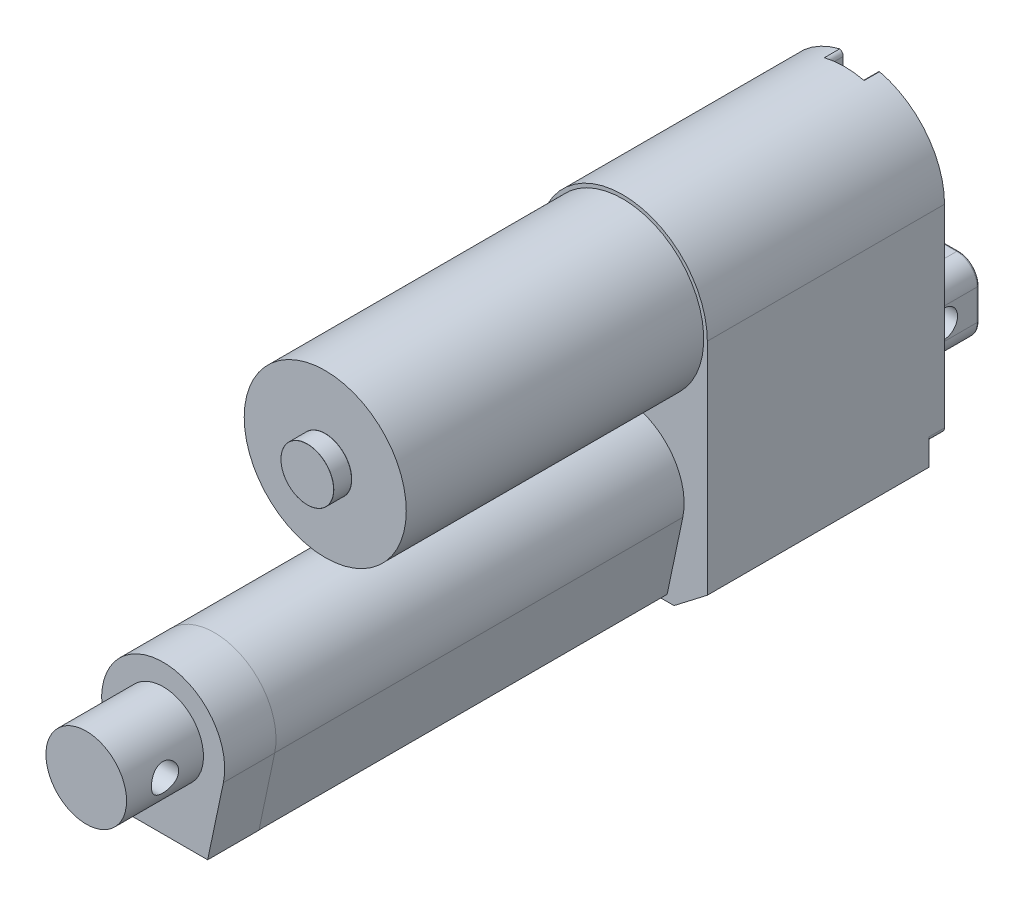
SolidWorks part; units mm, degrees
ref_plane "Front Plane" through (0, 0, 0) normal (0, 0, 1) x (1, 0, 0)
ref_plane "Top Plane" through (0, 0, 0) normal (0, 1, 0) x (1, 0, 0)
ref_plane "Right Plane" through (0, 0, 0) normal (1, 0, 0) x (0, 0, -1)
sketch "Sketch1" plane through (0, 0, 0) normal (0, 0, 1) x (1, 0, 0)
  line L0 (-12.7, 0) -> (12.7, 0)
  line L1 (-20.955, 6.35) -> (-20.955, 60.833)
  line L2 (20.955, 6.35) -> (20.955, 60.833)
  line L3 (12.7, 0) -> (20.955, 6.35)
  line L4 (-20.955, 6.35) -> (-12.7, 0)
  arc A0 (-20.955, 60.833) -> (20.955, 60.833) centre (0, 60.833) cw
  point P0 (0, 81.788)
  dimension "D7" = 81.788
  dimension "D1" = 41.91
  dimension "D2" = 8.255
  dimension "D3" = 12.7
  dimension "D4" = 8.255
  dimension "D5" = 12.7
  dimension "D6" = 6.35
extrude "Boss-Extrude1" add sketch "Sketch1" along normal blind 58.7375
sketch "Sketch2" plane through (0, 0, 58.7375) normal (0, 0, 1) x (1, 0, 0)
  circle A0 centre (0, 60.833) radius 20.066
  arc A1 (20.955, 60.833) -> (-20.955, 60.833) centre (0, 60.833) ccw construction
  dimension "D1" = 40.132
extrude "Boss-Extrude2" add sketch "Sketch2" along normal blind 73.66
sketch "Sketch3" plane through (0, 0, 58.7375) normal (0, 0, 1) x (1, 0, 0)
  line L0 (-12.7, 0) -> (12.7, 0) construction
  line L1 (-14.8881, 20.0427) -> (-10.9969, 1.5621)
  line L2 (-10.9969, 1.5621) -> (10.9969, 1.5621)
  line L3 (10.9969, 1.5621) -> (14.8881, 20.0427)
  line L5 (-10.9969, 1.5621) -> (-10.668, 0) construction
  line L6 (10.9969, 1.5621) -> (10.668, 0) construction
  arc A0 (14.8881, 20.0427) -> (-14.8881, 20.0427) centre (0, 23.1775) ccw
  point P1 (0, 1.5621)
  point P6 (15.2146, 23.1775)
  point P11 (-15.2146, 23.1775)
  point P16 (0, 38.3921)
  dimension "D1" = 23.1775
  dimension "D3" = 36.83
  dimension "D2" = 30.4292
  dimension "D4" = 21.336
extrude "EDIT_LENGTH_HERE (hover for comment)" add sketch "Sketch3" along normal blind 113.792
sketch "Sketch4" plane through (0, 0, 172.5295) normal (0, 0, 1) x (1, 0, 0)
  circle A0 centre (0, 23.1775) radius 9.9822
  arc A1 (14.8881, 20.0427) -> (-14.8881, 20.0427) centre (0, 23.1775) ccw construction
  dimension "D3" = 19.9644
extrude "Boss-Extrude4" add sketch "Sketch4" along normal blind 19.05
sketch "Sketch5" plane through (0, 0, 0) normal (0, 0, -1) x (-1, 0, 0)
  line L0 (12.7, 0) -> (-12.7, 0) construction
  line L1 (-3.81, 32.0675) -> (3.81, 32.0675)
  line L2 (-8.89, 26.9875) -> (-8.89, 19.3675)
  line L3 (-3.81, 14.2875) -> (3.81, 14.2875)
  line L4 (8.89, 26.9875) -> (8.89, 19.3675)
  line L5 (-8.89, 32.0675) -> (8.89, 14.2875) construction
  line L6 (-8.89, 14.2875) -> (8.89, 32.0675) construction
  arc A0 (-8.89, 19.3675) -> (-3.81, 14.2875) centre (-3.81, 19.3675) ccw
  arc A1 (3.81, 14.2875) -> (8.89, 19.3675) centre (3.81, 19.3675) ccw
  arc A2 (3.81, 32.0675) -> (8.89, 26.9875) centre (3.81, 26.9875) cw
  arc A3 (-3.81, 32.0675) -> (-8.89, 26.9875) centre (-3.81, 26.9875) ccw
  point P0 (0, 23.1775)
  dimension "D4" = 5.08
  dimension "D1" = 17.78
  dimension "D2" = 17.78
  dimension "D3" = 14.2875
extrude "Boss-Extrude5" add sketch "Sketch5" along normal blind 20.6502
sketch "Sketch6" plane through (8.89, 0, 0) normal (1, 0, 0) x (0, 0, -1)
  line L0 (11.9062, 14.2875) -> (11.9062, 32.0675) construction
  line L1 (0, 26.9875) -> (0, 19.3675) construction
  line L2 (20.6502, 14.2875) -> (0, 14.2875) construction
  line L3 (-191.5795, 33.1597) -> (-191.5795, 13.1953) construction
  line L4 (20.6502, 32.0675) -> (0, 32.0675) construction
  circle A0 centre (11.9062, 23.1775) radius 3.3782
  circle A1 centre (-182.0545, 23.1775) radius 3.3782
  dimension "D1" = 6.7564
  dimension "D3" = 6.7564
  dimension "D2" = 11.9062
  dimension "D4" = 9.525
extrude "Cut-Extrude3" cut sketch "Sketch6" against normal through all and the other way through all
fillet "Fillet1" radius 2.54 8 edges at (-7.4021, 15.7754, 0) (0, 14.2875, 0) (7.4021, 15.7754, 0) (8.89, 23.1775, 0) (7.4021, 30.5796, 0) (0, 32.0675, 0) (-7.4021, 30.5796, 0) (-8.89, 23.1775, 0)
fillet "Fillet2" radius 0.508 8 edges at (8.89, 23.1775, -20.6502) (7.4021, 30.5796, -20.6502) (0, 32.0675, -20.6502) (-7.4021, 30.5796, -20.6502) (-8.89, 23.1775, -20.6502) (-7.4021, 15.7754, -20.6502) (0, 14.2875, -20.6502) (7.4021, 15.7754, -20.6502)
sketch "Sketch7" plane through (0, 0, 0) normal (0, 0, -1) x (-1, 0, 0)
  line L0 (-4.1275, 77.089) -> (-4.1275, 80.0683)
  line L1 (4.1275, 77.089) -> (4.1275, 79.9786)
  line L2 (-20.955, 6.35) -> (-20.955, 60.833) construction
  line L3 (20.955, 60.833) -> (20.955, 6.35) construction
  line L4 (-13.3956, 1.8544) -> (-11.2223, 6.0477)
  line L5 (-14.605, 11.6109) -> (-19.685, 11.6109)
  line L6 (11.5416, 5.5356) -> (13.4023, 1.8413)
  line L7 (14.605, 11.6109) -> (19.685, 11.6109)
  line L8 (20.955, 6.35) -> (12.7, 0) construction
  line L9 (-12.7, 0) -> (-20.955, 6.35) construction
  line L10 (-20.955, 6.35) -> (-20.955, 12.8809)
  line L11 (12.7, 0) -> (-12.7, 0) construction
  line L12 (-12.7, 0) -> (-20.955, 6.35)
  line L13 (20.955, 12.8809) -> (20.955, 6.35)
  line L14 (20.955, 6.35) -> (12.7, 0)
  arc A0 (-4.1275, 77.089) -> (4.1275, 77.089) centre (0, 77.089) ccw
  arc A1 (20.955, 60.833) -> (-20.955, 60.833) centre (0, 60.833) ccw construction
  arc A2 (6.3689, 80.7967) -> (-6.4572, 80.7683) centre (0, 60.833) ccw
  arc A3 (-6.4572, 80.7683) -> (-4.1275, 80.0683) centre (-5.3975, 80.0683) cw
  arc A4 (4.1275, 79.9786) -> (6.3689, 80.7967) centre (5.3975, 79.9786) cw
  arc A5 (-11.2223, 6.0477) -> (-14.605, 11.6109) centre (-14.605, 7.8009) ccw
  arc A6 (14.605, 11.6109) -> (11.5416, 5.5356) centre (14.605, 7.8009) ccw
  arc A7 (13.4023, 1.8413) -> (12.268, 0) centre (12.268, 1.27) cw
  arc A8 (-13.3956, 1.8544) -> (-12.268, 0) centre (-12.268, 1.27) ccw
  arc A9 (19.685, 11.6109) -> (20.955, 12.8809) centre (19.685, 12.8809) ccw
  arc A10 (-19.685, 11.6109) -> (-20.955, 12.8809) centre (-19.685, 12.8809) cw
  point P12 (4.6513, 81.2653)
  point P39 (20.955, 11.6109)
  point P42 (-20.955, 11.6109)
  line M10 (20.955, 6.35) -> (20.955, 60.833)
  arc M11 (20.955, 60.833) -> (-20.955, 60.833) centre (0, 60.833) ccw
  line M12 (-20.955, 60.833) -> (-20.955, 6.35)
  line M13 (-20.955, 6.35) -> (-12.7, 0)
  dimension "D1" = 8.255
  dimension "D2" = 1.27
  dimension "D3" = 1.27
  dimension "D5" = 7.62
  dimension "D8" = 1.27
  dimension "D9" = 1.27
  dimension "D4" = 16.256
  dimension "D6" = 6.35
  dimension "D7" = 6.35
extrude "Cut-Extrude5" cut sketch "Sketch7" against normal blind 3.81 contours L1 A4 A3 L0 A0 M11 | L5 A10 A8 L4 A5 M12 M13 | A9 L7 A6 L6 A7 L14 M10
sketch "Sketch8" plane through (0, 0, 132.3975) normal (0, 0, 1) x (1, 0, 0)
  circle A0 centre (0, 60.833) radius 6.5405
  dimension "D1" = 13.081
extrude "Boss-Extrude6" add sketch "Sketch8" along normal blind 4.445
fillet "Fillet3" radius 0.0254 2 edges at (6.5405, 60.833, 132.3975) (6.5405, 60.833, 136.8425)
sketch "Sketch9" plane through (0, 0, 172.5295) normal (0, 0, 1) x (1, 0, 0)
  line L0 (10.9969, 1.5621) -> (14.8881, 20.0427) construction
  line L1 (-14.8881, 20.0427) -> (-10.9969, 1.5621) construction
  line L2 (-10.9969, 1.5621) -> (10.9969, 1.5621) construction
  line L3 (10.9969, 1.5621) -> (14.8881, 20.0427)
  line L4 (-14.8881, 20.0427) -> (-10.9969, 1.5621)
  line L5 (-10.9969, 1.5621) -> (10.9969, 1.5621)
  line L6 (-11.0175, 1.5367) -> (11.0175, 1.5367)
  line L7 (11.0175, 1.5367) -> (14.913, 20.0374)
  line L8 (-14.913, 20.0374) -> (-11.0175, 1.5367)
  arc A0 (14.8881, 20.0427) -> (-14.8881, 20.0427) centre (0, 23.1775) ccw construction
  arc A1 (14.8881, 20.0427) -> (-14.8881, 20.0427) centre (0, 23.1775) ccw
  arc A2 (14.913, 20.0374) -> (-14.913, 20.0374) centre (0, 23.1775) ccw
  dimension "D1" = 0.0254
extrude "Boss-Extrude7" add sketch "Sketch9" against normal blind 12.7
sketch "Sketch10" plane through (0, 0, 3.81) normal (0, 0, -1) x (-1, 0, 0)
  circle A0 centre (0, 77.089) radius 2.54
  circle A1 centre (-14.605, 7.8009) radius 2.54
  circle A2 centre (14.605, 7.8009) radius 2.54
  dimension "D1" = 5.08
extrude "Boss-Extrude8" add sketch "Sketch10" along normal blind 0.635
sketch "Sketch12" plane through (0, 0, 3.175) normal (0, 0, -1) x (-1, 0, 0)
  line L0 (0.3175, 74.3343) -> (0.3175, 75.8444)
  line L1 (-0.2921, 78.359) -> (0.2921, 78.359)
  line L2 (-0.3175, 78.3336) -> (-0.3175, 77.5335)
  line L3 (-0.2921, 75.819) -> (0.2921, 75.819)
  line L4 (0.3175, 78.3336) -> (0.3175, 77.5335)
  line L5 (-0.3175, 78.359) -> (0.3175, 75.819) construction
  line L6 (-0.3175, 75.819) -> (0.3175, 78.359) construction
  line L7 (-1.2446, 77.4065) -> (-0.4445, 77.4065)
  line L8 (-1.27, 77.3811) -> (-1.27, 76.7969)
  line L9 (-1.2446, 76.7715) -> (-0.4445, 76.7715)
  line L10 (1.27, 77.3811) -> (1.27, 76.7763)
  line L11 (-1.27, 77.4065) -> (1.27, 76.7715) construction
  line L12 (-1.27, 76.7715) -> (1.27, 77.4065) construction
  line L13 (0.3264, 74.381) -> (1.2682, 76.767)
  line L14 (-14.2875, 7.3564) -> (-14.2875, 6.5563)
  line L15 (0.4445, 77.4065) -> (1.2446, 77.4065)
  line L16 (-0.3175, 76.6445) -> (-0.3175, 75.8444)
  line L17 (-14.8971, 9.0709) -> (-14.3129, 9.0709)
  line L18 (-14.9225, 9.0455) -> (-14.9225, 8.2454)
  line L19 (-14.8971, 6.5309) -> (-14.3129, 6.5309)
  line L20 (-14.2875, 9.0455) -> (-14.2875, 8.2454)
  line L21 (-14.9225, 9.0709) -> (-14.2875, 6.5309) construction
  line L22 (-14.9225, 6.5309) -> (-14.2875, 9.0709) construction
  line L23 (-15.8496, 8.1184) -> (-15.0495, 8.1184)
  line L24 (-15.875, 8.093) -> (-15.875, 7.5088)
  line L25 (-15.8496, 7.4834) -> (-15.0495, 7.4834)
  line L26 (-13.335, 8.093) -> (-13.335, 7.5088)
  line L27 (-15.875, 8.1184) -> (-13.335, 7.4834) construction
  line L28 (-15.875, 7.4834) -> (-13.335, 8.1184) construction
  line L29 (-14.1605, 7.4834) -> (-13.3604, 7.4834)
  line L30 (-14.1605, 8.1184) -> (-13.3604, 8.1184)
  line L31 (-14.9225, 7.3564) -> (-14.9225, 6.5563)
  line L32 (14.9225, 7.3564) -> (14.9225, 6.5563)
  line L33 (14.3129, 9.0709) -> (14.8971, 9.0709)
  line L34 (14.2875, 9.0455) -> (14.2875, 8.2454)
  line L35 (14.3129, 6.5309) -> (14.8971, 6.5309)
  line L36 (14.9225, 9.0455) -> (14.9225, 8.2454)
  line L37 (14.2875, 9.0709) -> (14.9225, 6.5309) construction
  line L38 (14.2875, 6.5309) -> (14.9225, 9.0709) construction
  line L39 (13.3604, 8.1184) -> (14.1605, 8.1184)
  line L40 (13.335, 8.093) -> (13.335, 7.5088)
  line L41 (13.3604, 7.4834) -> (14.1605, 7.4834)
  line L42 (15.875, 8.093) -> (15.875, 7.5088)
  line L43 (13.335, 8.1184) -> (15.875, 7.4834) construction
  line L44 (13.335, 7.4834) -> (15.875, 8.1184) construction
  line L45 (15.0495, 7.4834) -> (15.8496, 7.4834)
  line L46 (15.0495, 8.1184) -> (15.8496, 8.1184)
  line L47 (14.2875, 7.3564) -> (14.2875, 6.5055)
  arc A0 (-0.4445, 76.7715) -> (-0.3175, 76.6445) centre (-0.4445, 76.6445) cw
  arc A1 (0.3264, 74.381) -> (0.3175, 74.3343) centre (0.4445, 74.3343) ccw
  arc A2 (0.3175, 77.5335) -> (0.4445, 77.4065) centre (0.4445, 77.5335) ccw
  arc A3 (-0.4445, 77.4065) -> (-0.3175, 77.5335) centre (-0.4445, 77.5335) ccw
  arc A4 (-1.2446, 77.4065) -> (-1.27, 77.3811) centre (-1.2446, 77.3811) ccw
  arc A5 (-1.27, 76.7969) -> (-1.2446, 76.7715) centre (-1.2446, 76.7969) ccw
  arc A6 (-0.3175, 75.8444) -> (-0.2921, 75.819) centre (-0.2921, 75.8444) ccw
  arc A7 (0.2921, 75.819) -> (0.3175, 75.8444) centre (0.2921, 75.8444) ccw
  arc A8 (1.2682, 76.767) -> (1.27, 76.7763) centre (1.2446, 76.7763) ccw
  arc A9 (1.2446, 77.4065) -> (1.27, 77.3811) centre (1.2446, 77.3811) cw
  arc A10 (0.2921, 78.359) -> (0.3175, 78.3336) centre (0.2921, 78.3336) cw
  arc A11 (-0.2921, 78.359) -> (-0.3175, 78.3336) centre (-0.2921, 78.3336) ccw
  arc A12 (-15.0495, 7.4834) -> (-14.9225, 7.3564) centre (-15.0495, 7.3564) cw
  arc A13 (-14.1605, 7.4834) -> (-14.2875, 7.3564) centre (-14.1605, 7.3564) ccw
  arc A14 (-14.2875, 8.2454) -> (-14.1605, 8.1184) centre (-14.1605, 8.2454) ccw
  arc A15 (-15.0495, 8.1184) -> (-14.9225, 8.2454) centre (-15.0495, 8.2454) ccw
  arc A16 (-15.8496, 8.1184) -> (-15.875, 8.093) centre (-15.8496, 8.093) ccw
  arc A17 (-15.875, 7.5088) -> (-15.8496, 7.4834) centre (-15.8496, 7.5088) ccw
  arc A18 (-14.9225, 6.5563) -> (-14.8971, 6.5309) centre (-14.8971, 6.5563) ccw
  arc A19 (-14.3129, 6.5309) -> (-14.2875, 6.5563) centre (-14.3129, 6.5563) ccw
  arc A20 (-13.3604, 7.4834) -> (-13.335, 7.5088) centre (-13.3604, 7.5088) ccw
  arc A21 (-13.3604, 8.1184) -> (-13.335, 8.093) centre (-13.3604, 8.093) cw
  arc A22 (-14.3129, 9.0709) -> (-14.2875, 9.0455) centre (-14.3129, 9.0455) cw
  arc A23 (-14.8971, 9.0709) -> (-14.9225, 9.0455) centre (-14.8971, 9.0455) ccw
  arc A26 (14.1605, 7.4834) -> (14.2875, 7.3564) centre (14.1605, 7.3564) cw
  arc A27 (15.0495, 7.4834) -> (14.9225, 7.3564) centre (15.0495, 7.3564) ccw
  arc A28 (14.9225, 8.2454) -> (15.0495, 8.1184) centre (15.0495, 8.2454) ccw
  arc A29 (14.1605, 8.1184) -> (14.2875, 8.2454) centre (14.1605, 8.2454) ccw
  arc A30 (13.3604, 8.1184) -> (13.335, 8.093) centre (13.3604, 8.093) ccw
  arc A31 (13.335, 7.5088) -> (13.3604, 7.4834) centre (13.3604, 7.5088) ccw
  arc A32 (14.2875, 6.5055) -> (14.3129, 6.5309) centre (14.3129, 6.5055) ccw
  arc A33 (14.8971, 6.5309) -> (14.9225, 6.5563) centre (14.8971, 6.5563) ccw
  arc A34 (15.8496, 7.4834) -> (15.875, 7.5088) centre (15.8496, 7.5088) ccw
  arc A35 (15.8496, 8.1184) -> (15.875, 8.093) centre (15.8496, 8.093) cw
  arc A36 (14.8971, 9.0709) -> (14.9225, 9.0455) centre (14.8971, 9.0455) cw
  arc A37 (14.3129, 9.0709) -> (14.2875, 9.0455) centre (14.3129, 9.0455) ccw
  point P0 (0, 77.089)
  point P6 (0, 77.089)
  point P16 (-0.3175, 76.7715)
  point P20 (0.3175, 74.3585)
  point P23 (0.3175, 77.4065)
  point P50 (-14.605, 7.8009)
  point P55 (-14.605, 7.8009)
  point P96 (14.605, 7.8009)
  point P101 (14.605, 7.8009)
  dimension "D5" = 0.127
  dimension "D6" = 0.0254
  dimension "D11" = 0.127
  dimension "D12" = 0.0254
  dimension "D17" = 0.127
  dimension "D18" = 0.0254
  dimension "D1" = 0.635
  dimension "D2" = 2.54
  dimension "D3" = 0.635
  dimension "D4" = 2.54
  dimension "D7" = 0.635
  dimension "D8" = 2.54
  dimension "D9" = 0.635
  dimension "D10" = 2.54
  dimension "D13" = 0.635
  dimension "D14" = 2.54
  dimension "D15" = 0.635
  dimension "D16" = 2.54
dome "Dome1" [suppressed] faces to dome 3 distance 1.27 parameters "D1"=1.27
extrude "Cut-Extrude7" [suppressed] cut sketch "Sketch12" along normal up to next
